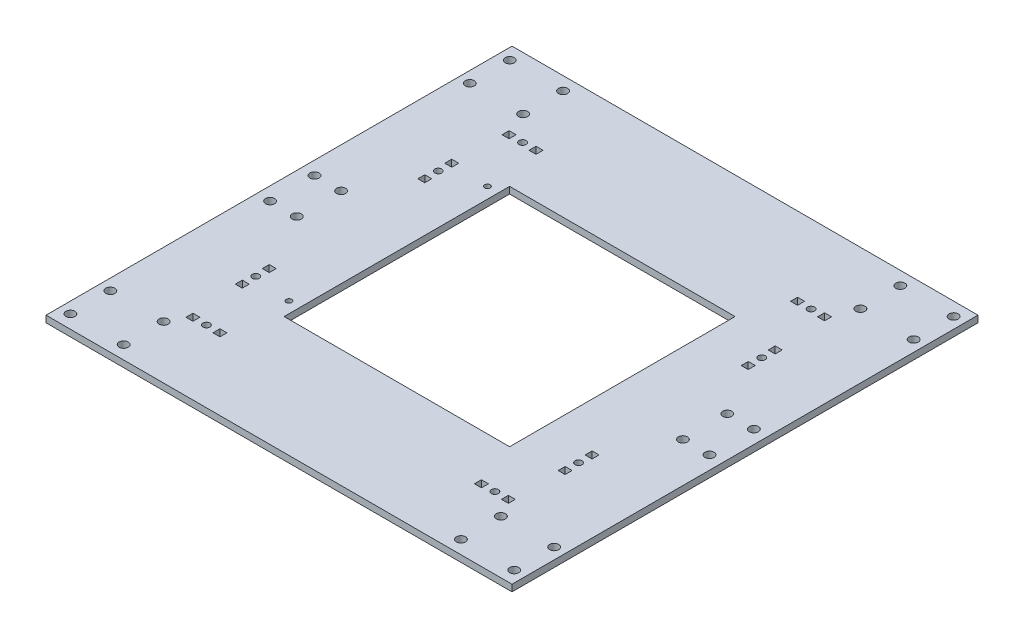
SolidWorks part; units mm, degrees
ref_plane "Front Plane" through (0, 0, 0) normal (0, 0, 1) x (1, 0, 0)
ref_plane "Top Plane" through (0, 0, 0) normal (0, 1, 0) x (1, 0, 0)
ref_plane "Right Plane" through (0, 0, 0) normal (1, 0, 0) x (0, 0, -1)
sketch "Sketch2" plane through (0, 0, 0) normal (0, 1, 0) x (1, 0, 0)
  line L0 (0, 0) -> (0, 210)
  line L1 (0, 210) -> (210, 210)
  line L2 (210, 210) -> (210, 0)
  line L3 (54.2, 154.719) -> (155.8, 154.719)
  line L4 (54.2, 53.119) -> (54.2, 154.719)
  line L5 (155.8, 53.119) -> (54.2, 53.119)
  line L6 (210, 0) -> (0, 0)
  line L7 (179.455, 140.15) -> (176.305, 137) construction
  line L8 (0, 105) -> (50000, 105) construction
  line L9 (105, 30) -> (105, 50030) construction
  line L10 (30.545, 149.15) -> (33.695, 149.15)
  line L11 (30.545, 149.15) -> (30.545, 152.3)
  line L12 (12, 210) -> (12, 0) construction
  line L13 (155.8, 154.719) -> (155.8, 53.119)
  line L14 (30.545, 152.3) -> (33.695, 152.3)
  line L15 (33.695, 149.15) -> (33.695, 152.3)
  line L16 (30.545, 137) -> (33.695, 137)
  line L17 (18, 115) -> (6, 115.0001) construction
  line L18 (6, 115.0001) -> (6, 95) construction
  line L19 (18.0001, 95) -> (6, 95) construction
  line L20 (30.545, 137) -> (30.545, 140.15)
  line L21 (198, 210) -> (198, 0) construction
  line L22 (30.545, 140.15) -> (33.695, 140.15)
  line L23 (33.695, 137) -> (33.695, 140.15)
  line L24 (30.545, 137) -> (33.695, 140.15) construction
  line L25 (30.545, 140.15) -> (33.695, 137) construction
  line L26 (30.545, 66.91) -> (33.695, 66.91)
  line L27 (30.545, 66.91) -> (30.545, 70.06)
  line L28 (30.545, 70.06) -> (33.695, 70.06)
  line L29 (33.695, 66.91) -> (33.695, 70.06)
  line L30 (30.545, 66.91) -> (33.695, 70.06) construction
  line L31 (30.545, 70.06) -> (33.695, 66.91) construction
  line L32 (30.545, 54.76) -> (33.695, 54.76)
  line L33 (30.545, 54.76) -> (30.545, 57.91)
  line L34 (30.545, 57.91) -> (33.695, 57.91)
  line L35 (33.695, 54.76) -> (33.695, 57.91)
  line L36 (30.545, 54.76) -> (33.695, 57.91) construction
  line L37 (30.545, 57.91) -> (33.695, 54.76) construction
  line L38 (176.025, 66.91) -> (179.175, 66.91)
  line L39 (176.025, 66.91) -> (176.025, 70.06)
  line L40 (176.025, 70.06) -> (179.175, 70.06)
  line L41 (179.175, 66.91) -> (179.175, 70.06)
  line L42 (176.025, 66.91) -> (179.175, 70.06) construction
  line L43 (176.025, 70.06) -> (179.175, 66.91) construction
  line L44 (176.025, 57.91) -> (179.175, 57.91)
  line L45 (176.025, 57.91) -> (176.025, 54.76)
  line L46 (176.025, 54.76) -> (179.175, 54.76)
  line L47 (179.175, 57.91) -> (179.175, 54.76)
  line L48 (176.025, 57.91) -> (179.175, 54.76) construction
  line L49 (176.025, 54.76) -> (179.175, 57.91) construction
  line L50 (179.455, 137) -> (176.305, 140.15) construction
  line L51 (176.305, 137) -> (176.305, 140.15)
  line L52 (179.455, 140.15) -> (176.305, 140.15)
  line L53 (179.455, 137) -> (179.455, 140.15)
  line L54 (179.455, 137) -> (176.305, 137)
  line L55 (176.305, 149.15) -> (176.305, 152.3)
  line L56 (179.455, 152.3) -> (176.305, 152.3)
  line L57 (179.455, 149.15) -> (179.455, 152.3)
  line L58 (179.455, 149.15) -> (176.305, 149.15)
  line L59 (165.5, 176.335) -> (162.35, 173.185) construction
  line L60 (32.35, 30.725) -> (35.5, 30.725)
  line L61 (32.35, 30.725) -> (32.35, 33.875)
  line L62 (32.35, 33.875) -> (35.5, 33.875)
  line L63 (35.5, 30.725) -> (35.5, 33.875)
  line L64 (32.35, 30.725) -> (35.5, 33.875) construction
  line L65 (32.35, 33.875) -> (35.5, 30.725) construction
  line L66 (44.5, 30.725) -> (47.65, 30.725)
  line L67 (44.5, 30.725) -> (44.5, 33.875)
  line L68 (44.5, 33.875) -> (47.65, 33.875)
  line L69 (47.65, 30.725) -> (47.65, 33.875)
  line L70 (44.5, 30.725) -> (47.65, 33.875) construction
  line L71 (44.5, 33.875) -> (47.65, 30.725) construction
  line L72 (35.5, 173.185) -> (32.35, 173.185)
  line L73 (35.5, 173.185) -> (35.5, 176.335)
  line L74 (35.5, 176.335) -> (32.35, 176.335)
  line L75 (32.35, 173.185) -> (32.35, 176.335)
  line L76 (35.5, 173.185) -> (32.35, 176.335) construction
  line L77 (35.5, 176.335) -> (32.35, 173.185) construction
  line L78 (44.5, 173.185) -> (47.65, 173.185)
  line L79 (44.5, 173.185) -> (44.5, 176.335)
  line L80 (44.5, 176.335) -> (47.65, 176.335)
  line L81 (47.65, 173.185) -> (47.65, 176.335)
  line L82 (44.5, 173.185) -> (47.65, 176.335) construction
  line L83 (177.65, 33.875) -> (174.5, 30.725) construction
  line L84 (177.65, 30.725) -> (174.5, 33.875) construction
  line L85 (174.5, 30.725) -> (174.5, 33.875)
  line L86 (177.65, 33.875) -> (174.5, 33.875)
  line L87 (177.65, 30.725) -> (177.65, 33.875)
  line L88 (177.65, 30.725) -> (174.5, 30.725)
  line L89 (165.5, 33.875) -> (162.35, 30.725) construction
  line L90 (165.5, 30.725) -> (162.35, 33.875) construction
  line L91 (162.35, 30.725) -> (162.35, 33.875)
  line L92 (165.5, 33.875) -> (162.35, 33.875)
  line L93 (165.5, 30.725) -> (165.5, 33.875)
  line L94 (165.5, 30.725) -> (162.35, 30.725)
  line L95 (44.5, 176.335) -> (47.65, 173.185) construction
  line L96 (165.5, 173.185) -> (162.35, 176.335) construction
  line L97 (174.5, 176.335) -> (177.65, 173.185) construction
  line L98 (174.5, 173.185) -> (177.65, 176.335) construction
  line L99 (162.35, 173.185) -> (162.35, 176.335)
  line L100 (165.5, 176.335) -> (162.35, 176.335)
  line L101 (165.5, 173.185) -> (165.5, 176.335)
  line L102 (165.5, 173.185) -> (162.35, 173.185)
  line L103 (177.65, 173.185) -> (177.65, 176.335)
  line L104 (174.5, 176.335) -> (177.65, 176.335)
  line L105 (174.5, 173.185) -> (174.5, 176.335)
  line L106 (174.5, 173.185) -> (177.65, 173.185)
  circle A0 centre (5, 24) radius 2.05
  circle A1 centre (29, 24) radius 2.05
  circle A2 centre (40, 32.3) radius 1.575
  circle A3 centre (205, 6) radius 2.05
  circle A4 centre (181, 6) radius 2.05
  circle A5 centre (170, 32.3) radius 1.575
  circle A6 centre (29, 6) radius 2.05
  circle A7 centre (5, 6) radius 2.05
  circle A8 centre (181, 24) radius 2.05
  circle A9 centre (205, 24) radius 2.05
  circle A10 centre (205, 186) radius 2.05
  circle A11 centre (181, 186) radius 2.05
  circle A12 centre (40, 174.76) radius 1.575
  circle A13 centre (181, 204) radius 2.05
  circle A14 centre (205, 204) radius 2.05
  circle A15 centre (5, 204) radius 2.05
  circle A16 centre (29, 204) radius 2.05
  circle A17 centre (170, 174.76) radius 1.575
  circle A18 centre (29, 186) radius 2.05
  circle A19 centre (5, 186) radius 2.05
  circle A20 centre (177.6, 62.41) radius 1.575
  circle A21 centre (177.88, 144.65) radius 1.575
  circle A28 centre (32.12, 144.65) radius 1.575
  circle A29 centre (32.12, 62.41) radius 1.575
  circle A32 centre (49.2, 149.719) radius 1.25
  circle A33 centre (49.2, 60.281) radius 1.25
  circle A34 centre (18.0001, 95) radius 2.05
  circle A35 centre (18, 115) radius 2.05
  circle A36 centre (6, 115.0001) radius 2.05
  circle A37 centre (6, 95) radius 2.05
  circle A38 centre (204, 95) radius 2.05
  circle A39 centre (204, 115.0001) radius 2.05
  circle A40 centre (191.9999, 95) radius 2.05
  circle A41 centre (192, 115) radius 2.05
  point P6 (105, 0)
  point P11 (0, 105)
  point P33 (33.925, 32.3)
  point P34 (32.12, 138.575)
  point P51 (46.075, 174.76)
  point P52 (33.925, 174.76)
  point P61 (32.12, 56.335)
  point P66 (32.12, 68.485)
  point P79 (46.075, 32.3)
  point P83 (177.6, 68.485)
  point P84 (0, 0)
  point P91 (105, 154.719)
  point P116 (177.6, 56.335)
  point P121 (0, 0)
  point P122 (0, 0)
  point P123 (0, 0)
  point P155 (176.075, 32.3)
  point P160 (163.925, 32.3)
  point P169 (176.075, 174.76)
  point P170 (163.925, 174.76)
  point P171 (177.88, 138.575)
  point P172 (0, 0)
  point P173 (179.0064, 61.85)
  dimension "D7" = 4.1
  dimension "D8" = 4.1
  dimension "D9" = 4.1
  dimension "D10" = 18
  dimension "D11" = 24
  dimension "D12" = 2.5
  dimension "D13" = 5
  dimension "D14" = 6
  dimension "D15" = 3.15
  dimension "D16" = 11
  dimension "D17" = 32.3
  dimension "D6" = 4.1
  dimension "D20" = 101.6
  dimension "D18" = 41.35
  dimension "D21" = 3.12
  dimension "D23" = 3.15
  dimension "D24" = 38.41
  dimension "D29" = 20
  dimension "D32" = 6
  dimension "D22" = 12
  dimension "D36" = 4.5
  dimension "D19" = 3.15
  dimension "D28" = 12
  dimension "D30" = 10
  dimension "D41" = 4.1
  dimension "D42" = 4.1
  dimension "D43" = 4.1
  dimension "D44" = 4.1
  dimension "D33" = 3.15
  dimension "D57" = 3.15
  dimension "D70" = 3.15
  dimension "D1" = 210
  dimension "D4" = 101.6
  dimension "D5" = 210
  dimension "D25" = 3.12
  dimension "D26" = 5
  dimension "D27" = 5
  dimension "D31" = 12.0001
  dimension "D34" = 3.15
  dimension "D35" = 4.5
  dimension "D37" = 3.15
  dimension "D38" = 3.15
  dimension "D39" = 1.575
  dimension "D40" = 20.0001
  dimension "D45" = 3.15
  dimension "D46" = 3.15
  dimension "D47" = 3.15
  dimension "D48" = 3.15
  dimension "D49" = 4.5
  dimension "D50" = 4.5
  dimension "D51" = 4.5
  dimension "D52" = 3.15
  dimension "D53" = 3.15
  dimension "D54" = 3.15
  dimension "D55" = 3.15
  dimension "D56" = 4.5
  dimension "D58" = 4.5
  dimension "D59" = 4.5
  dimension "D60" = 3.15
  dimension "D61" = 3.15
  dimension "D62" = 3.15
  dimension "D63" = 3.15
  dimension "D64" = 11.24
  dimension "D65" = 3.15
  dimension "D66" = 4.5
  dimension "D67" = 4.5
  dimension "D68" = 3.15
  dimension "D69" = 3.15
  dimension "D71" = 38.41
  dimension "D72" = 3.4
  dimension "D73" = 3.15
  dimension "D74" = 18.466
extrude "Boss-Extrude2" add sketch "Sketch2" against normal blind 3
sketch "Sketch3" [suppressed] plane through (0, 0, 0) normal (0, 1, 0) x (1, 0, 0)
  line L0 (172.5, 172.5) -> (172.5, 37.5) construction
  line L1 (37.5, 172.5) -> (172.5, 172.5) construction
  line L2 (172.5, 37.5) -> (37.5, 37.5) construction
  circle A0 centre (177.75, 146.25) radius 1.575
  circle A2 centre (177.75, 64) radius 1.575
  dimension "D1" = 3.15
  dimension "D3" = 26.25
  dimension "D4" = 3.15
  dimension "D2" = 5.25
  dimension "D5" = 5.25
  dimension "D6" = 26.5
extrude "Cut-Extrude1" [suppressed] cut sketch "Sketch3" against normal blind 10
sketch "Sketch4" [suppressed] plane through (0, 0, 0) normal (0, 1, 0) x (1, 0, 0)
  line L0 (105, -841.9) -> (105, 49158.1) construction
  line L1 (172.5, 172.5) -> (37.5, 172.5) construction
  line L2 (37.5, 37.5) -> (37.5, 172.5) construction
  line L3 (172.5, 37.5) -> (37.5, 37.5) construction
  line L4 (37.5, 172.5) -> (172.5, 172.5) construction
  circle A0 centre (32.25, 146.25) radius 1.575
  circle A1 centre (32.25, 64) radius 1.575
  point P5 (105, 172.5)
  dimension "D1" = 3.15
  dimension "D2" = 3.15
  dimension "D3" = 26.5
  dimension "D4" = 26.25
  dimension "D5" = 5.25
  dimension "D6" = 5.25
extrude "Cut-Extrude2" [suppressed] cut sketch "Sketch4" against normal blind 10
